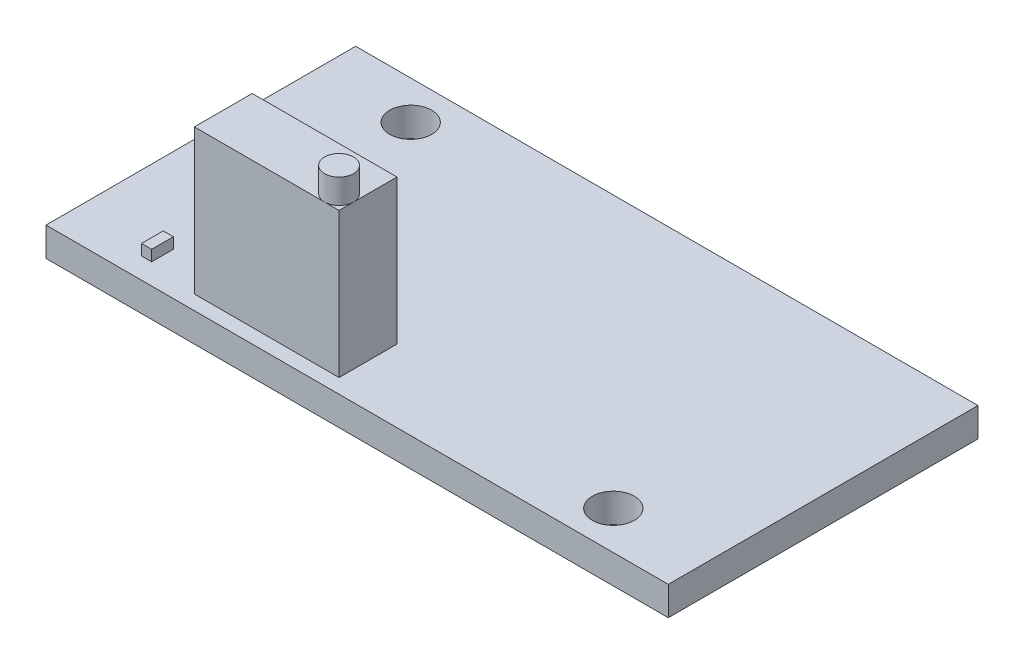
SolidWorks part; units mm, degrees
ref_plane "Front Plane" through (0, 0, 0) normal (0, 0, 1) x (1, 0, 0)
ref_plane "Top Plane" through (0, 0, 0) normal (0, 1, 0) x (1, 0, 0)
ref_plane "Right Plane" through (0, 0, 0) normal (1, 0, 0) x (0, 0, -1)
sketch "Sketch1" plane through (0, 0, 0) normal (0, 1, 0) x (1, 0, 0)
  line L1 (-21.5, -10.7) -> (21.5, -10.7)
  line L2 (-21.5, -10.7) -> (-21.5, 10.7)
  line L3 (-21.5, 10.7) -> (21.5, 10.7)
  line L4 (21.5, -10.7) -> (21.5, 10.7)
  line L5 (-21.5, -10.7) -> (21.5, 10.7) construction
  line L6 (-21.5, 10.7) -> (21.5, -10.7) construction
  point P0 (0, 0)
  dimension "D1" = 43
  dimension "D2" = 21.4
extrude "Boss-Extrude1" add sketch "Sketch1" along normal blind 2
sketch "Sketch2" plane through (0, 2, 0) normal (0, 1, 0) x (1, 0, 0)
  line L1 (-21.5, 10.7) -> (-21.5, -10.7) construction
  line L2 (21.5, -10.7) -> (21.5, 10.7) construction
  line L3 (21.5, 10.7) -> (-21.5, 10.7) construction
  line L4 (-21.5, -10.7) -> (21.5, -10.7) construction
  circle A0 centre (-15.05, 8.05) radius 1.45
  circle A1 centre (15.05, -8.05) radius 1.45
  dimension "D3" = 2.9
  dimension "D6" = 2.9
  dimension "D1" = 6.45
  dimension "D2" = 6.45
  dimension "D4" = 2.65
  dimension "D5" = 2.65
extrude "Cut-Extrude1" cut sketch "Sketch2" against normal through all
sketch "Sketch3" plane through (0, 2, 0) normal (0, 1, 0) x (1, 0, 0)
  line L1 (-2.25, -9.7) -> (-12.25, -9.7)
  line L2 (-2.25, -9.7) -> (-2.25, -5.7)
  line L3 (-2.25, -5.7) -> (-12.25, -5.7)
  line L4 (-12.25, -9.7) -> (-12.25, -5.7)
  line L5 (-2.25, -9.7) -> (-12.25, -5.7) construction
  line L6 (-2.25, -5.7) -> (-12.25, -9.7) construction
  line L7 (-21.5, -10.7) -> (21.5, -10.7) construction
  circle A1 centre (-15.05, 8.05) radius 1.45 construction
  point P0 (-7.25, -7.7)
  dimension "D1" = 2.8
  dimension "D2" = 10
  dimension "D3" = 4
  dimension "D4" = 1
extrude "Boss-Extrude2" add sketch "Sketch3" along normal blind 10
sketch "Sketch4" plane through (0, 12, 0) normal (0, 1, 0) x (1, 0, 0)
  line L2 (-2.25, -9.7) -> (-2.25, -5.7) construction
  line L3 (-12.25, -9.7) -> (-2.25, -9.7) construction
  circle A0 centre (-3.25, -8.7) radius 1
  dimension "D1" = 2
  dimension "D2" = 1
  dimension "D3" = 1
extrude "Boss-Extrude3" add sketch "Sketch4" along normal blind 1.7
sketch "Sketch5" plane through (0, 2, 0) normal (0, 1, 0) x (1, 0, 0)
  line L0 (-21.5, 10.7) -> (-21.5, -10.7) construction
  line L1 (-15.65, -7.75) -> (-16.35, -7.75)
  line L2 (-15.65, -7.75) -> (-15.65, -9.25)
  line L3 (-15.65, -9.25) -> (-16.35, -9.25)
  line L4 (-16.35, -7.75) -> (-16.35, -9.25)
  line L5 (-15.65, -7.75) -> (-16.35, -9.25) construction
  line L6 (-15.65, -9.25) -> (-16.35, -7.75) construction
  line L7 (-21.5, -10.7) -> (21.5, -10.7) construction
  point P0 (-16, -8.5)
  point P9 (-26.1883, -9.6532)
  dimension "D1" = 5.5
  dimension "D2" = 2.2
  dimension "D3" = 0.7
  dimension "D4" = 1.5
extrude "Boss-Extrude4" add sketch "Sketch5" along normal blind 0.75
